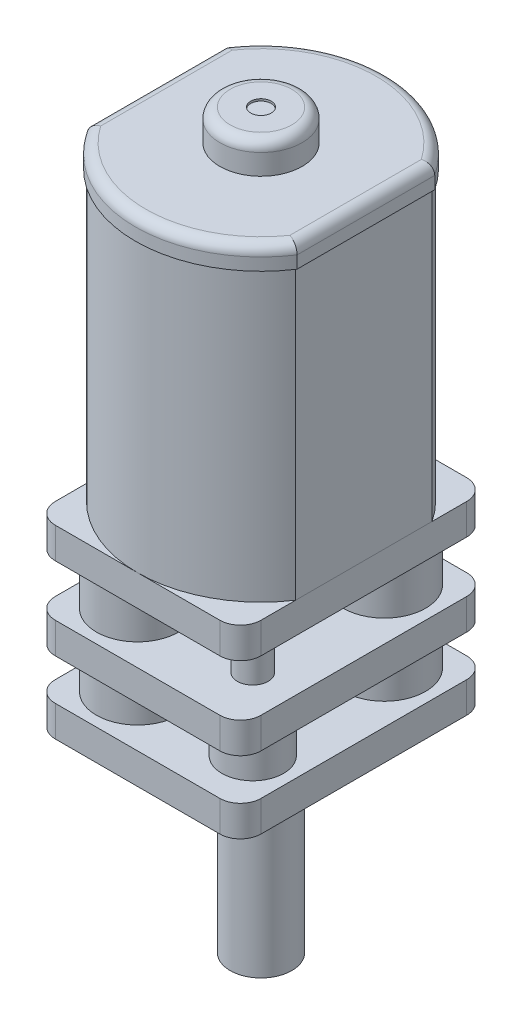
SolidWorks part; units mm, degrees
ref_plane "前视基准面" through (0, 0, 0) normal (0, 0, 1) x (1, 0, 0)
ref_plane "上视基准面" through (0, 0, 0) normal (0, 1, 0) x (1, 0, 0)
ref_plane "右视基准面" through (0, 0, 0) normal (1, 0, 0) x (0, 0, -1)
sketch "草图1" plane through (0, 0, 0) normal (0, 1, 0) x (1, 0, 0)
  line L0 (0, 0) -> (0, 12.552) construction
  line L1 (-5, 3.3166) -> (-5, -3.3166)
  line L2 (5, 3.3166) -> (5, -3.3166)
  arc A0 (-5, -3.3166) -> (5, -3.3166) centre (0, 0) ccw
  arc A1 (5, 3.3166) -> (-5, 3.3166) centre (0, 0) ccw
  dimension "D1" = 6
  dimension "D2" = 10
extrude "凸台-拉伸1" add sketch "草图1" against normal blind 15
sketch "草图2" plane through (0, 0, 0) normal (0, 1, 0) x (1, 0, 0)
  circle A0 centre (0, 0) radius 2
  circle A1 centre (0, 0) radius 0.5
  dimension "D1" = 1
  dimension "D2" = 4
extrude "凸台-拉伸2" add sketch "草图2" along normal blind 1.6
sketch "草图3" plane through (0, 0, 0) normal (0, 1, 0) x (1, 0, 0)
  circle A1 centre (0, 0) radius 0.5
  circle A2 centre (0, 0) radius 0.5
  dimension "D1" = 0
extrude "凸台-拉伸3" add sketch "草图3" along normal blind 1.5
sketch "草图4" plane through (0, -15, 0) normal (0, -1, 0) x (1, 0, 0)
  line L0 (-5, -3.3166) -> (-5, 3.3166) construction
  line L1 (5, -6) -> (-5, -6)
  line L2 (5, -6) -> (5, 6)
  line L3 (5, 6) -> (-5, 6)
  line L4 (-5, -6) -> (-5, 6)
  line L5 (5, -6) -> (-5, 6) construction
  line L6 (5, 6) -> (-5, -6) construction
  point P1 (0, 0)
  dimension "D1" = 12
extrude "凸台-拉伸4" add sketch "草图4" along normal blind 9 separate body
sketch "草图5" plane through (0, -24, 0) normal (0, -1, 0) x (1, 0, 0)
  circle A0 centre (0, 0) radius 1.5
  dimension "D1" = 3
extrude "凸台-拉伸5" add sketch "草图5" along normal blind 10
sketch "草图6" plane through (0, -24, 0) normal (0, -1, 0) x (1, 0, 0)
  circle A0 centre (0, 0) radius 2
  circle A1 centre (0, 0) radius 1.5 construction
  circle A2 centre (0, 0) radius 1.5
  dimension "D1" = 4
extrude "凸台-拉伸6" add sketch "草图6" along normal blind 1
sketch "草图7" plane through (-5, 0, 0) normal (-1, 0, 0) x (0, 0, 1)
  line L0 (-6, -24) -> (-6, -15) construction
  line L1 (-6, -22.5) -> (6, -22.5)
  line L2 (-6, -22.5) -> (-6, -16.5)
  line L3 (-6, -16.5) -> (6, -16.5)
  line L4 (6, -22.5) -> (6, -16.5)
  line L5 (6, -24) -> (6, -15) construction
  line L6 (6, -24) -> (-6, -24) construction
  line L8 (-6, -15) -> (6, -15) construction
  line L9 (6, -24) -> (6, -15) construction
  dimension "D1" = 1.5
  dimension "D2" = 1.5
extrude "切除-拉伸1" cut sketch "草图7" against normal blind 20
sketch "草图8" plane through (0, -16.5, 0) normal (0, -1, 0) x (1, 0, 0)
  line L0 (5, -6) -> (5, 6) construction
  line L1 (-5, -6) -> (5, -6) construction
  line L2 (-5, 6) -> (-5, -6) construction
  line L3 (5, 6) -> (-5, 6) construction
  circle A0 centre (0, 0) radius 1
  circle A1 centre (2.5, -3.5) radius 2
  circle A2 centre (-2.5, 3.5) radius 2
  dimension "D1" = 2
  dimension "D2" = 4
  dimension "D3" = 4
  dimension "D5" = 2.5
  dimension "D6" = 2.5
  dimension "D7" = 2.5
  dimension "D4" = 2.5
extrude "凸台-拉伸7" add sketch "草图8" along normal blind 7
ref_plane "基准面1" through (0, -20.5, 0) normal (0, -1, 0) x (-1, 0, 0)
sketch "草图10" plane through (0, -20.5, 0) normal (0, -1, 0) x (-1, 0, 0)
  line L0 (-5, 6) -> (-5, -6) construction
  line L1 (-5, -6) -> (5, -6) construction
  circle A0 centre (0, 0) radius 3
  circle A1 centre (-3, -3.4) radius 1.5
  dimension "D1" = 3
  dimension "D2" = 6
  dimension "D3" = 2
  dimension "D4" = 2.6
extrude "凸台-拉伸8" add sketch "草图10" along normal blind 2
sketch "草图11" plane through (0, -20.5, 0) normal (0, 1, 0) x (1, 0, 0)
  circle A0 centre (3, -3.4) radius 0.75
  dimension "D1" = 1.5
extrude "凸台-拉伸9" add sketch "草图11" along normal blind 4
sketch "草图12" plane through (0, 0, 0) normal (0, 1, 0) x (1, 0, 0)
  line L0 (-5.1, 3.3466) -> (-5.1, -3.3466)
  line L1 (5.1, -3.3466) -> (5.1, 3.3466)
  line L2 (-5, 3.3166) -> (-5, -3.3166)
  line L3 (5, -3.3166) -> (5, 3.3166)
  line L4 (-5, 3.3166) -> (-5, -3.3166)
  line L5 (5, -3.3166) -> (5, 3.3166)
  arc A0 (5.1, 3.3466) -> (-5.1, 3.3466) centre (0, 0) ccw
  arc A1 (-5.1, -3.3466) -> (5.1, -3.3466) centre (0, 0) ccw
  arc A2 (5, 3.3166) -> (-5, 3.3166) centre (0, 0) ccw
  arc A3 (-5, -3.3166) -> (5, -3.3166) centre (0, 0) ccw
  arc A4 (5, 3.3166) -> (-5, 3.3166) centre (0, 0) ccw
  arc A5 (-5, -3.3166) -> (5, -3.3166) centre (0, 0) ccw
  dimension "D1" = 0
  dimension "D2" = 0.1
extrude "凸台-拉伸10" add sketch "草图12" against normal blind 1
sketch "草图13" plane through (0, 0, 0) normal (0, 1, 0) x (1, 0, 0)
  line L2 (-5.1, 3.3466) -> (-5.1, -3.3466)
  line L3 (5.1, -3.3466) -> (5.1, 3.3466)
  line L4 (-5.1, 3.3466) -> (-5.1, -3.3466)
  line L5 (5.1, -3.3466) -> (5.1, 3.3466)
  arc A2 (5.1, 3.3466) -> (-5.1, 3.3466) centre (0, 0) ccw
  arc A3 (-5.1, -3.3466) -> (5.1, -3.3466) centre (0, 0) ccw
  arc A4 (5.1, 3.3466) -> (-5.1, 3.3466) centre (0, 0) ccw
  arc A5 (-5.1, -3.3466) -> (5.1, -3.3466) centre (0, 0) ccw
  dimension "D1" = 0
extrude "凸台-拉伸11" add sketch "草图13" along normal blind 0.1
fillet "圆角1" radius 0.5 4 edges at (0, 0.1, -6.1) (0, 0.1, 6.1) (-5.1, 0.1, 0) (5.1, 0.1, 0)
fillet "圆角2" radius 0.5 1 edges at (0, 1.6, 2)
sketch "草图14" plane through (0, -20.5, 0) normal (0, 1, 0) x (1, 0, 0)
  line L4 (5, 6) -> (-5, 6)
  line L5 (-5, 6) -> (-5, -6)
  line L6 (-5, -6) -> (5, -6)
  line L7 (5, -6) -> (5, 6)
  line L8 (5, 6) -> (-5, 6)
  line L9 (-5, 6) -> (-5, -6)
  line L10 (-5, -6) -> (5, -6)
  line L11 (5, -6) -> (5, 6)
  dimension "D1" = 0
extrude "凸台-拉伸12" add sketch "草图14" along normal blind 1.5
fillet "圆角3" radius 1 12 edges at (5, -15.75, 6) (5, -19.75, 6) (5, -23.25, 6) (5, -23.25, -6) (5, -15.75, -6) (5, -19.75, -6) (-5, -23.25, -6) (-5, -19.75, -6) (-5, -15.75, -6) (-5, -15.75, 6) (-5, -23.25, 6) (-5, -19.75, 6)
